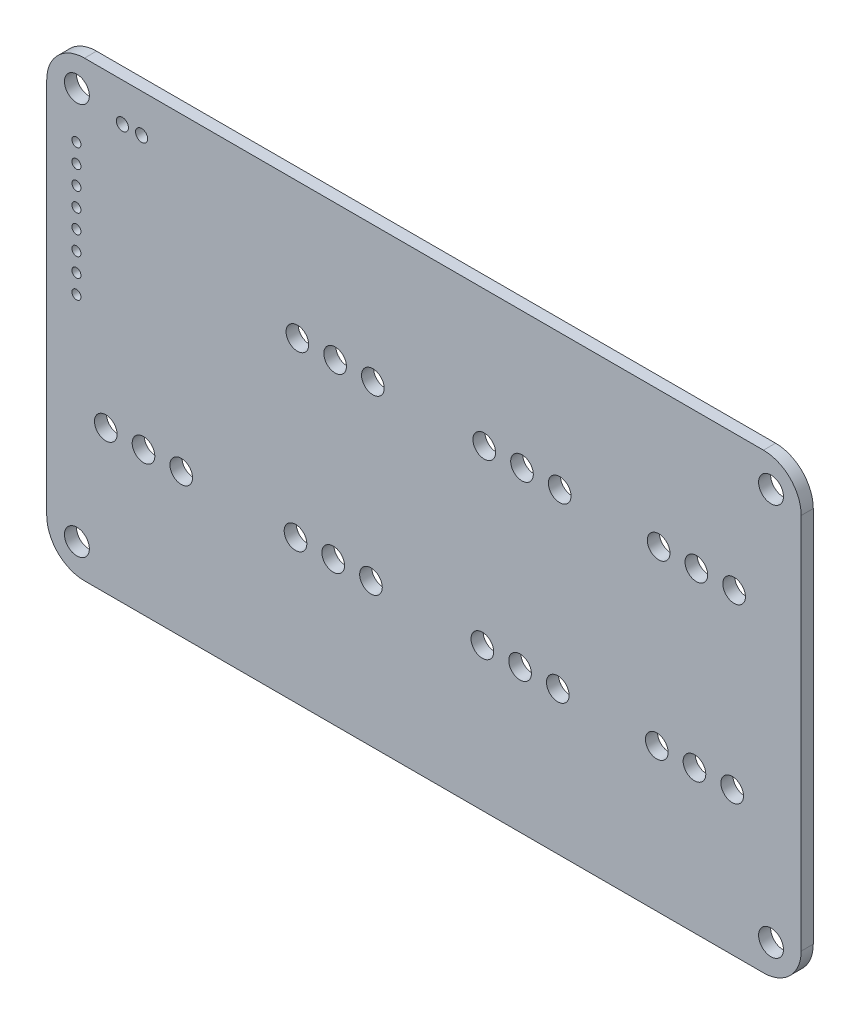
SolidWorks part; units mm, degrees
ref_plane "Front Plane" through (0, 0, 0) normal (0, 0, 1) x (1, 0, 0)
ref_plane "Top Plane" through (0, 0, 0) normal (0, 1, 0) x (1, 0, 0)
ref_plane "Right Plane" through (0, 0, 0) normal (1, 0, 0) x (0, 0, -1)
sketch "BoardOutLine" plane through (0, 0, 0) normal (0, 0, 1) x (1, 0, 0)
  line L0 (0, -55) -> (0, -5)
  line L1 (95, -60) -> (5, -60)
  line L2 (100, -5) -> (100, -55)
  line L3 (5, 0) -> (95, 0)
  line L4 (1.4645, -1.4645) -> (98.5355, -58.5355) construction
  arc A0 (100, -5) -> (95, 0) centre (95, -5) ccw
  arc A1 (95, -60) -> (100, -55) centre (95, -55) ccw
  arc A2 (0, -55) -> (5, -60) centre (5, -55) ccw
  arc A3 (5, 0) -> (0, -5) centre (5, -5) ccw
  point P14 (0, 0)
  point P15 (0, 0)
  point P16 (0, 0)
  dimension "D3" = 5
  dimension "D1" = 90
  dimension "D2" = 50
extrude "Boss-Extrude1" add sketch "BoardOutLine" along normal blind 1.6
sketch "Multi-Layer" plane through (0, 0, 1.6) normal (0, 0, 1) x (1, 0, 0)
  line L0 (95, 0) -> (5, 0) construction
  line L1 (0, -5) -> (0, -55) construction
  circle A1 centre (3.937, -25.173) radius 0.6
  circle A3 centre (3.937, -22.6731) radius 0.6
  circle A5 centre (3.937, -20.173) radius 0.6
  circle A7 centre (3.937, -17.6731) radius 0.6
  circle A9 centre (3.937, -15.173) radius 0.6
  circle A11 centre (3.937, -12.6731) radius 0.6
  circle A13 centre (3.937, -10.173) radius 0.6
  circle A15 centre (32.9743, -41.0211) radius 1.5
  circle A17 centre (37.9731, -41.0211) radius 1.5
  circle A19 centre (42.9743, -41.0211) radius 1.5
  circle A21 centre (57.7394, -41.0211) radius 1.5
  circle A23 centre (62.7381, -41.0211) radius 1.5
  circle A25 centre (67.7394, -41.0211) radius 1.5
  circle A27 centre (80.8534, -41.0211) radius 1.5
  circle A29 centre (85.8522, -41.0211) radius 1.5
  circle A31 centre (90.8534, -41.0211) radius 1.5
  circle A33 centre (43.2258, -18.034) radius 1.5
  circle A35 centre (38.2271, -18.034) radius 1.5
  circle A37 centre (33.2258, -18.034) radius 1.5
  circle A39 centre (67.9909, -18.034) radius 1.5
  circle A41 centre (62.9921, -18.034) radius 1.5
  circle A43 centre (57.9909, -18.034) radius 1.5
  circle A45 centre (91.1049, -18.034) radius 1.5
  circle A47 centre (86.1062, -18.034) radius 1.5
  circle A49 centre (81.1049, -18.034) radius 1.5
  circle A51 centre (10.033, -5.08) radius 0.8
  circle A53 centre (12.573, -5.08) radius 0.8
  circle A55 centre (7.8283, -41.0211) radius 1.5
  circle A57 centre (12.827, -41.0211) radius 1.5
  circle A59 centre (17.8283, -41.0211) radius 1.5
  circle A60 centre (3.937, -27.6731) radius 0.6
  circle A61 centre (4, -4) radius 1.65
  circle A62 centre (96, -56) radius 1.65
  circle A63 centre (96, -4) radius 1.65
  circle A64 centre (4, -56) radius 1.65
  point P0 (0, 0)
  point P24 (0, 0)
  point P25 (0, 0)
  point P29 (0, 0)
  point P32 (0, 0)
  point P47 (0, 0)
  point P50 (0, 0)
  point P53 (0, 0)
  point P56 (0, 0)
  point P95 (0, 0)
  point P107 (0, 0)
  point P108 (0, 0)
  dimension "D1" = 3.3
  dimension "D3" = 4
  dimension "D4" = 92
  dimension "D5" = 52
  dimension "D6" = 1.6
  dimension "D7" = 2.54
  dimension "D2" = 4
  dimension "D8" = 5.08
  dimension "D9" = 10.033
extrude "Cut-Extrude2" cut sketch "Multi-Layer" against normal up to next (1.6 mm away)
sketch "TopSilkLayer" plane through (0, 0, 0) normal (0, 0, 1) x (1, 0, 0)
  line L0 (1.587, -7.703) -> (1.587, -30.143)
  line L1 (1.587, -30.143) -> (7.337, -30.143)
  line L2 (7.337, -30.143) -> (7.337, -7.703)
  line L3 (7.337, -7.703) -> (1.587, -7.703)
  line L4 (1.651, -13.589) -> (2.159, -13.589)
  line L5 (2.159, -13.589) -> (2.159, -24.257)
  line L6 (2.159, -24.257) -> (1.651, -24.257)
  line L7 (37.7191, -32.3851) -> (49.1491, -32.3851)
  line L8 (49.1491, -32.3851) -> (49.1491, -40.5131)
  line L9 (49.1491, -40.5131) -> (49.1491, -43.3071)
  line L10 (49.1491, -43.3071) -> (27.0511, -43.3071)
  line L11 (27.0511, -43.3071) -> (27.0511, -32.3851)
  line L12 (27.0511, -32.3851) -> (37.7191, -32.3851)
  line L13 (35.4331, -43.3071) -> (34.1631, -43.3071)
  line L14 (34.1631, -43.3071) -> (34.1631, -49.1491)
  line L15 (34.1631, -49.1491) -> (42.0371, -49.1491)
  line L16 (42.0371, -49.1491) -> (42.0371, -43.3071)
  line L17 (42.0371, -43.3071) -> (40.5131, -43.3071)
  line L18 (36.1951, -49.1491) -> (35.4331, -49.1491)
  line L19 (35.4331, -49.1491) -> (35.4331, -59.0551)
  line L20 (35.4331, -59.0551) -> (40.5131, -59.0551)
  line L21 (40.5131, -59.0551) -> (40.5131, -49.1491)
  line L22 (40.5131, -49.1491) -> (39.7511, -49.1491)
  line L23 (62.4841, -32.3851) -> (73.9141, -32.3851)
  line L24 (73.9141, -32.3851) -> (73.9141, -40.5131)
  line L25 (73.9141, -40.5131) -> (73.9141, -43.3071)
  line L26 (73.9141, -43.3071) -> (51.8161, -43.3071)
  line L27 (51.8161, -43.3071) -> (51.8161, -32.3851)
  line L28 (51.8161, -32.3851) -> (62.4841, -32.3851)
  line L29 (60.1981, -43.3071) -> (58.9281, -43.3071)
  line L30 (58.9281, -43.3071) -> (58.9281, -49.1491)
  line L31 (58.9281, -49.1491) -> (66.8021, -49.1491)
  line L32 (66.8021, -49.1491) -> (66.8021, -43.3071)
  line L33 (66.8021, -43.3071) -> (65.2781, -43.3071)
  line L34 (60.9601, -49.1491) -> (60.1981, -49.1491)
  line L35 (60.1981, -49.1491) -> (60.1981, -59.0551)
  line L36 (60.1981, -59.0551) -> (65.2781, -59.0551)
  line L37 (65.2781, -59.0551) -> (65.2781, -49.1491)
  line L38 (65.2781, -49.1491) -> (64.5161, -49.1491)
  line L39 (85.5982, -32.3851) -> (97.0282, -32.3851)
  line L40 (97.0282, -32.3851) -> (97.0282, -40.5131)
  line L41 (97.0282, -40.5131) -> (97.0282, -43.3071)
  line L42 (97.0282, -43.3071) -> (74.9301, -43.3071)
  line L43 (74.9301, -43.3071) -> (74.9301, -32.3851)
  line L44 (74.9301, -32.3851) -> (85.5982, -32.3851)
  line L45 (83.3122, -43.3071) -> (82.0422, -43.3071)
  line L46 (82.0422, -43.3071) -> (82.0422, -49.1491)
  line L47 (82.0422, -49.1491) -> (89.9162, -49.1491)
  line L48 (89.9162, -49.1491) -> (89.9162, -43.3071)
  line L49 (89.9162, -43.3071) -> (88.3922, -43.3071)
  line L50 (84.0742, -49.1491) -> (83.3122, -49.1491)
  line L51 (83.3122, -49.1491) -> (83.3122, -59.0551)
  line L52 (83.3122, -59.0551) -> (88.3922, -59.0551)
  line L53 (88.3922, -59.0551) -> (88.3922, -49.1491)
  line L54 (88.3922, -49.1491) -> (87.6302, -49.1491)
  line L55 (38.4811, -26.6701) -> (27.0511, -26.6701)
  line L56 (27.0511, -26.6701) -> (27.0511, -18.542)
  line L57 (27.0511, -18.542) -> (27.0511, -15.748)
  line L58 (27.0511, -15.748) -> (49.1491, -15.748)
  line L59 (49.1491, -15.748) -> (49.1491, -26.6701)
  line L60 (49.1491, -26.6701) -> (38.4811, -26.6701)
  line L61 (40.7671, -15.748) -> (42.0371, -15.748)
  line L62 (42.0371, -15.748) -> (42.0371, -9.906)
  line L63 (42.0371, -9.906) -> (34.1631, -9.906)
  line L64 (34.1631, -9.906) -> (34.1631, -15.748)
  line L65 (34.1631, -15.748) -> (35.6871, -15.748)
  line L66 (40.0051, -9.906) -> (40.7671, -9.906)
  line L67 (40.7671, -9.906) -> (40.7671, 0)
  line L68 (40.7671, 0) -> (35.6871, 0)
  line L69 (35.6871, 0) -> (35.6871, -9.906)
  line L70 (35.6871, -9.906) -> (36.4491, -9.906)
  line L71 (63.2461, -26.6701) -> (51.8161, -26.6701)
  line L72 (51.8161, -26.6701) -> (51.8161, -18.542)
  line L73 (51.8161, -18.542) -> (51.8161, -15.748)
  line L74 (51.8161, -15.748) -> (73.9141, -15.748)
  line L75 (73.9141, -15.748) -> (73.9141, -26.6701)
  line L76 (73.9141, -26.6701) -> (63.2461, -26.6701)
  line L77 (65.5321, -15.748) -> (66.8021, -15.748)
  line L78 (66.8021, -15.748) -> (66.8021, -9.906)
  line L79 (66.8021, -9.906) -> (58.9281, -9.906)
  line L80 (58.9281, -9.906) -> (58.9281, -15.748)
  line L81 (58.9281, -15.748) -> (60.4521, -15.748)
  line L82 (64.7701, -9.906) -> (65.5321, -9.906)
  line L83 (65.5321, -9.906) -> (65.5321, 0)
  line L84 (65.5321, 0) -> (60.4521, 0)
  line L85 (60.4521, 0) -> (60.4521, -9.906)
  line L86 (60.4521, -9.906) -> (61.2141, -9.906)
  line L87 (86.3602, -26.6701) -> (74.9301, -26.6701)
  line L88 (74.9301, -26.6701) -> (74.9301, -18.542)
  line L89 (74.9301, -18.542) -> (74.9301, -15.748)
  line L90 (74.9301, -15.748) -> (97.0282, -15.748)
  line L91 (97.0282, -15.748) -> (97.0282, -26.6701)
  line L92 (97.0282, -26.6701) -> (86.3602, -26.6701)
  line L93 (88.6462, -15.748) -> (89.9162, -15.748)
  line L94 (89.9162, -15.748) -> (89.9162, -9.906)
  line L95 (89.9162, -9.906) -> (82.0422, -9.906)
  line L96 (82.0422, -9.906) -> (82.0422, -15.748)
  line L97 (82.0422, -15.748) -> (83.5662, -15.748)
  line L98 (87.8842, -9.906) -> (88.6462, -9.906)
  line L99 (88.6462, -9.906) -> (88.6462, 0)
  line L100 (88.6462, 0) -> (83.5662, 0)
  line L101 (83.5662, 0) -> (83.5662, -9.906)
  line L102 (83.5662, -9.906) -> (84.3282, -9.906)
  line L103 (12.1282, -2.7901) -> (12.1282, -1.9011)
  line L104 (8.509, -7.489) -> (14.097, -7.489)
  line L105 (8.509, -2.79) -> (14.097, -2.79)
  line L106 (10.795, -1.901) -> (10.795, -2.79)
  line L107 (13.335, -1.901) -> (13.335, -2.79)
  line L108 (9.5882, -2.79) -> (9.5882, -1.901)
  line L109 (8.509, -6.727) -> (14.097, -6.727)
  line L110 (8.509, -1.8029) -> (14.097, -1.8029)
  line L111 (14.097, -1.8029) -> (14.097, -8.2799)
  line L112 (14.097, -8.2799) -> (8.509, -8.2799)
  line L113 (8.509, -8.2799) -> (8.509, -1.8029)
  line L114 (12.573, -32.3851) -> (24.003, -32.3851)
  line L115 (24.003, -32.3851) -> (24.003, -40.5131)
  line L116 (24.003, -40.5131) -> (24.003, -43.3071)
  line L117 (24.003, -43.3071) -> (1.905, -43.3071)
  line L118 (1.905, -43.3071) -> (1.905, -32.3851)
  line L119 (1.905, -32.3851) -> (12.573, -32.3851)
  line L120 (10.287, -43.3071) -> (9.017, -43.3071)
  line L121 (9.017, -43.3071) -> (9.017, -49.1491)
  line L122 (9.017, -49.1491) -> (16.891, -49.1491)
  line L123 (16.891, -49.1491) -> (16.891, -43.3071)
  line L124 (16.891, -43.3071) -> (15.367, -43.3071)
  line L125 (11.049, -49.1491) -> (10.287, -49.1491)
  line L126 (10.287, -49.1491) -> (10.287, -59.0551)
  line L127 (10.287, -59.0551) -> (15.367, -59.0551)
  line L128 (15.367, -59.0551) -> (15.367, -49.1491)
  line L129 (15.367, -49.1491) -> (14.605, -49.1491)
  line L130 (8.001, -18.923) -> (8.001, -21.9949) construction
  line L131 (38.2271, -26.9241) -> (36.2625, -26.9241) construction
  line L132 (62.9921, -26.9241) -> (61.0276, -26.9241) construction
  line L133 (86.1062, -26.9241) -> (84.1416, -26.9241) construction
  arc A0 (34.1631, -43.8151) -> (42.0371, -44.5771) centre (39.4416, -30.3336) ccw
  arc A1 (34.1631, -44.8311) -> (42.0371, -45.5931) centre (39.4417, -31.3489) ccw
  arc A2 (34.1631, -45.8471) -> (42.0371, -46.6091) centre (39.4417, -32.3649) ccw
  arc A3 (34.1631, -46.8631) -> (42.0371, -47.6251) centre (39.4417, -33.3809) ccw
  arc A4 (35.4331, -50.4191) -> (40.5131, -51.4351) centre (38.8045, -46.7699) ccw
  arc A5 (35.4331, -51.6891) -> (40.5131, -52.7051) centre (38.8045, -48.04) ccw
  arc A6 (35.4331, -52.9591) -> (40.5131, -53.9751) centre (38.8045, -49.31) ccw
  arc A7 (35.4331, -53.9751) -> (40.5131, -54.9911) centre (38.8045, -50.326) ccw
  arc A8 (35.4331, -55.2451) -> (40.5131, -56.2611) centre (38.8045, -51.596) ccw
  arc A9 (35.4331, -56.2611) -> (40.5131, -57.2771) centre (38.8045, -52.612) ccw
  arc A10 (27.0511, -32.6391) -> (49.1491, -32.3851) centre (37.799, -6.3159) ccw
  arc A11 (58.9281, -43.8151) -> (66.8021, -44.5771) centre (64.2067, -30.3336) ccw
  arc A12 (58.9281, -44.8311) -> (66.8021, -45.5931) centre (64.2067, -31.3489) ccw
  arc A13 (58.9281, -45.8471) -> (66.8021, -46.6091) centre (64.2067, -32.3649) ccw
  arc A14 (58.9281, -46.8631) -> (66.8021, -47.6251) centre (64.2067, -33.3809) ccw
  arc A15 (60.1981, -50.4191) -> (65.2781, -51.4351) centre (63.5696, -46.7699) ccw
  arc A16 (60.1981, -51.6891) -> (65.2781, -52.7051) centre (63.5695, -48.04) ccw
  arc A17 (60.1981, -52.9591) -> (65.2781, -53.9751) centre (63.5695, -49.31) ccw
  arc A18 (60.1981, -53.9751) -> (65.2781, -54.9911) centre (63.5695, -50.326) ccw
  arc A19 (60.1981, -55.2451) -> (65.2781, -56.2611) centre (63.5695, -51.596) ccw
  arc A20 (60.1981, -56.2611) -> (65.2781, -57.2771) centre (63.5695, -52.612) ccw
  arc A21 (51.8161, -32.6391) -> (73.9141, -32.3851) centre (62.564, -6.3159) ccw
  arc A22 (82.0422, -43.8151) -> (89.9162, -44.5771) centre (87.3207, -30.3336) ccw
  arc A23 (82.0422, -44.8311) -> (89.9162, -45.5931) centre (87.3208, -31.3489) ccw
  arc A24 (82.0422, -45.8471) -> (89.9162, -46.6091) centre (87.3208, -32.3649) ccw
  arc A25 (82.0422, -46.8631) -> (89.9162, -47.6251) centre (87.3208, -33.3809) ccw
  arc A26 (83.3122, -50.4191) -> (88.3922, -51.4351) centre (86.6836, -46.7699) ccw
  arc A27 (83.3122, -51.6891) -> (88.3922, -52.7051) centre (86.6836, -48.04) ccw
  arc A28 (83.3122, -52.9591) -> (88.3922, -53.9751) centre (86.6836, -49.31) ccw
  arc A29 (83.3122, -53.9751) -> (88.3922, -54.9911) centre (86.6836, -50.326) ccw
  arc A30 (83.3122, -55.2451) -> (88.3922, -56.2611) centre (86.6836, -51.596) ccw
  arc A31 (83.3122, -56.2611) -> (88.3922, -57.2771) centre (86.6836, -52.612) ccw
  arc A32 (74.9301, -32.6391) -> (97.0282, -32.3851) centre (85.6781, -6.3159) ccw
  arc A33 (42.0371, -15.24) -> (34.1631, -14.478) centre (36.7585, -28.7215) ccw
  arc A34 (42.0371, -14.224) -> (34.1631, -13.462) centre (36.7585, -27.7062) ccw
  arc A35 (42.0371, -13.208) -> (34.1631, -12.446) centre (36.7585, -26.6902) ccw
  arc A36 (42.0371, -12.192) -> (34.1631, -11.43) centre (36.7585, -25.6742) ccw
  arc A37 (40.7671, -8.636) -> (35.6871, -7.62) centre (37.3956, -12.2852) ccw
  arc A38 (40.7671, -7.366) -> (35.6871, -6.35) centre (37.3957, -11.0151) ccw
  arc A39 (40.7671, -6.096) -> (35.6871, -5.08) centre (37.3957, -9.7451) ccw
  arc A40 (40.7671, -5.08) -> (35.6871, -4.064) centre (37.3957, -8.7291) ccw
  arc A41 (40.7671, -3.81) -> (35.6871, -2.794) centre (37.3957, -7.4591) ccw
  arc A42 (40.7671, -2.794) -> (35.6871, -1.778) centre (37.3957, -6.4431) ccw
  arc A43 (49.1491, -26.4161) -> (27.0511, -26.6701) centre (38.4012, -52.7392) ccw
  arc A44 (66.8021, -15.24) -> (58.9281, -14.478) centre (61.5236, -28.7215) ccw
  arc A45 (66.8021, -14.224) -> (58.9281, -13.462) centre (61.5235, -27.7062) ccw
  arc A46 (66.8021, -13.208) -> (58.9281, -12.446) centre (61.5235, -26.6902) ccw
  arc A47 (66.8021, -12.192) -> (58.9281, -11.43) centre (61.5235, -25.6742) ccw
  arc A48 (65.5321, -8.636) -> (60.4521, -7.62) centre (62.1607, -12.2852) ccw
  arc A49 (65.5321, -7.366) -> (60.4521, -6.35) centre (62.1607, -11.0151) ccw
  arc A50 (65.5321, -6.096) -> (60.4521, -5.08) centre (62.1607, -9.7451) ccw
  arc A51 (65.5321, -5.08) -> (60.4521, -4.064) centre (62.1607, -8.7291) ccw
  arc A52 (65.5321, -3.81) -> (60.4521, -2.794) centre (62.1607, -7.4591) ccw
  arc A53 (65.5321, -2.794) -> (60.4521, -1.778) centre (62.1607, -6.4431) ccw
  arc A54 (73.9141, -26.4161) -> (51.8161, -26.6701) centre (63.1662, -52.7392) ccw
  arc A55 (89.9162, -15.24) -> (82.0422, -14.478) centre (84.6376, -28.7215) ccw
  arc A56 (89.9162, -14.224) -> (82.0422, -13.462) centre (84.6376, -27.7062) ccw
  arc A57 (89.9162, -13.208) -> (82.0422, -12.446) centre (84.6376, -26.6902) ccw
  arc A58 (89.9162, -12.192) -> (82.0422, -11.43) centre (84.6376, -25.6742) ccw
  arc A59 (88.6462, -8.636) -> (83.5662, -7.62) centre (85.2747, -12.2852) ccw
  arc A60 (88.6462, -7.366) -> (83.5662, -6.35) centre (85.2748, -11.0151) ccw
  arc A61 (88.6462, -6.096) -> (83.5662, -5.08) centre (85.2748, -9.7451) ccw
  arc A62 (88.6462, -5.08) -> (83.5662, -4.064) centre (85.2748, -8.7291) ccw
  arc A63 (88.6462, -3.81) -> (83.5662, -2.794) centre (85.2748, -7.4591) ccw
  arc A64 (88.6462, -2.794) -> (83.5662, -1.778) centre (85.2748, -6.4431) ccw
  arc A65 (97.0282, -26.4161) -> (74.9301, -26.6701) centre (86.2803, -52.7392) ccw
  arc A66 (9.017, -43.8151) -> (16.891, -44.5771) centre (14.2956, -30.3336) ccw
  arc A67 (9.017, -44.8311) -> (16.891, -45.5931) centre (14.2956, -31.3489) ccw
  arc A68 (9.017, -45.8471) -> (16.891, -46.6091) centre (14.2956, -32.3649) ccw
  arc A69 (9.017, -46.8631) -> (16.891, -47.6251) centre (14.2956, -33.3809) ccw
  arc A70 (10.287, -50.4191) -> (15.367, -51.4351) centre (13.6585, -46.7699) ccw
  arc A71 (10.287, -51.6891) -> (15.367, -52.7051) centre (13.6584, -48.04) ccw
  arc A72 (10.287, -52.9591) -> (15.367, -53.9751) centre (13.6584, -49.31) ccw
  arc A73 (10.287, -53.9751) -> (15.367, -54.9911) centre (13.6584, -50.326) ccw
  arc A74 (10.287, -55.2451) -> (15.367, -56.2611) centre (13.6584, -51.596) ccw
  arc A75 (10.287, -56.2611) -> (15.367, -57.2771) centre (13.6584, -52.612) ccw
  arc A76 (1.905, -32.6391) -> (24.003, -32.3851) centre (12.6529, -6.3159) ccw
  circle A77 centre (10.033, -5.08) radius 1.0851
  circle A78 centre (12.573, -5.08) radius 1.0851
  text T0 "CN1" font "ARIAL" height 1.143
  text T1 "U2" font "ARIAL" height 1.143
  text T2 "U3" font "ARIAL" height 1.143
  text T3 "U4" font "ARIAL" height 1.143
  text T4 "U5" font "ARIAL" height 1.143
  text T5 "U6" font "ARIAL" height 1.143
  text T6 "U7" font "ARIAL" height 1.143
  text T7 "VIN" font "ARIAL" height 1.143
  text T8 "U1" font "ARIAL" height 1.143
